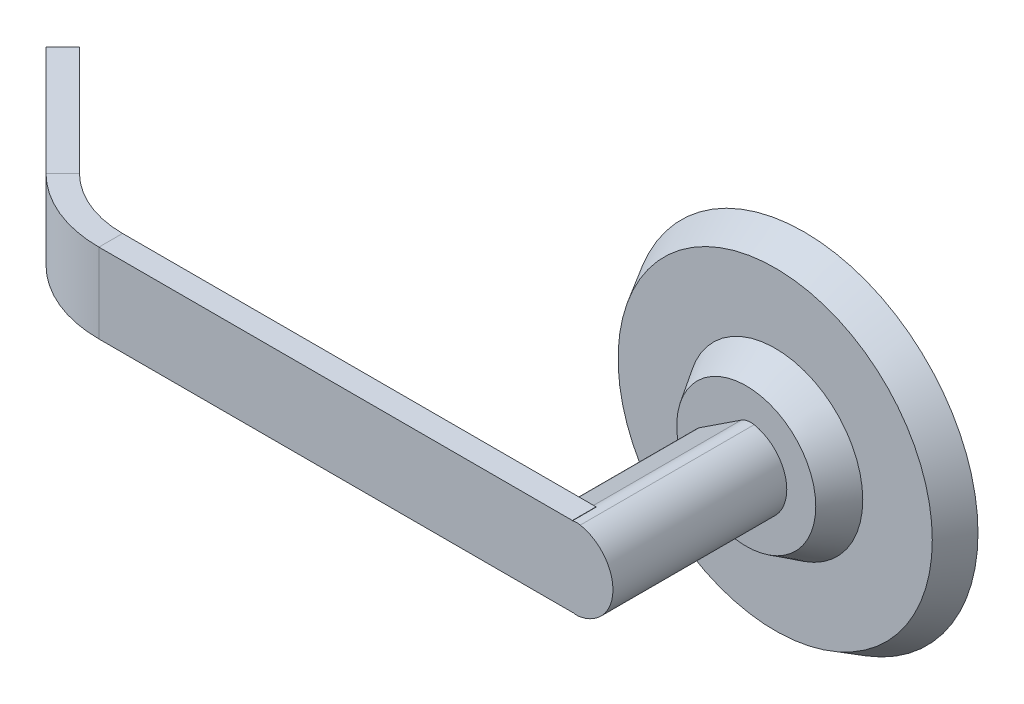
SolidWorks part; units mm, degrees
material "Nickel"
ref_plane "Front Plane" through (0, 0, 0) normal (0, 0, 1) x (1, 0, 0)
ref_plane "Top Plane" through (0, 0, 0) normal (0, 1, 0) x (1, 0, 0)
ref_plane "Right Plane" through (0, 0, 0) normal (1, 0, 0) x (0, 0, -1)
sketch "Sketch1" plane through (0, 0, 0) normal (0, 1, 0) x (1, 0, 0)
  line L0 (0, 0) -> (0, 12.7)
  line L1 (0, 12.7) -> (38.1, 12.7)
  line L2 (38.1, 12.7) -> (34.4338, 6.35)
  line L3 (34.4338, 6.35) -> (19.1938, 6.35)
  line L4 (19.1938, 6.35) -> (15.24, 0)
  line L5 (15.24, 0) -> (0, 0)
  dimension "D1" = 12.7
  dimension "D2" = 38.1
  dimension "D3" = 6.35
  dimension "D4" = 15.24
  dimension "D5" = 15.24
  dimension "D6" = 120
revolve "Revolve1" add sketch "Sketch1" angle 360 about L0
sketch "Sketch2" plane through (0, 0, 0) normal (0, 0, 1) x (1, 0, 0)
  line L0 (0, 0) -> (-69.9612, 0) construction
  line L3 (-1.1019, 8.1649) -> (-10.2862, 2.1219)
  line L4 (-10.2862, -2.1219) -> (-1.1019, -8.1649)
  arc A0 (1.7365, 8.7187) -> (1.7365, -8.7187) centre (0, 0) cw
  arc A1 (-10.2862, -2.1219) -> (-10.2862, 2.1219) centre (-8.89, 0) cw
  arc A2 (-1.1019, -8.1649) -> (1.7365, -8.7187) centre (0.9923, -4.9821) ccw
  arc A3 (-1.1019, 8.1649) -> (1.7365, 8.7187) centre (0.9923, 4.9821) cw
  point P8 (-13.511, 0)
  point P11 (0, -8.89)
  point P14 (0, 8.89)
  point P15 (0, 0)
  dimension "D1" = 8.89
  dimension "D2" = 2.54
  dimension "D4" = 3.81
  dimension "D3" = 8.89
extrude "Boss-Extrude1" add sketch "Sketch2" along normal blind 38.1 contours L4 A2 A0 A3 L3 A1
sketch "Sketch3" plane through (0, 0, 0) normal (1, 0, 0) x (0, 0, -1)
  line L0 (-38.1, -8.7187) -> (0, -8.7187) construction
  line L1 (-38.1, 8.7187) -> (-32.9143, 8.7187)
  line L2 (-38.1, 8.7187) -> (-38.1, -8.7187)
  line L3 (-38.1, -8.7187) -> (-32.9143, -8.7187)
  line L4 (-32.9143, 8.7187) -> (-32.9143, -8.7187)
  point P4 (-35.5072, 0)
  point P8 (0, 0)
  point P10 (0, 0)
  dimension "D1" = 5.1857
  dimension "D2" = 35.5072
sketch "Sketch4" plane through (0, 0, 0) normal (0, 1, 0) x (1, 0, 0)
  line L0 (0, -35.5072) -> (-103.779, -35.5072)
  line L1 (-121.7395, -28.0677) -> (-145.7309, -4.0763)
  arc A0 (-121.7395, -28.0677) -> (-103.779, -35.5072) centre (-103.779, -10.1072) ccw
  point P6 (-114.3, -35.5072)
  dimension "D4" = 25.4
  dimension "D1" = 114.3
  dimension "D2" = 44.45
  dimension "D3" = 135
sweep "Sweep1" add profiles "Sketch3" path "Sketch4"
